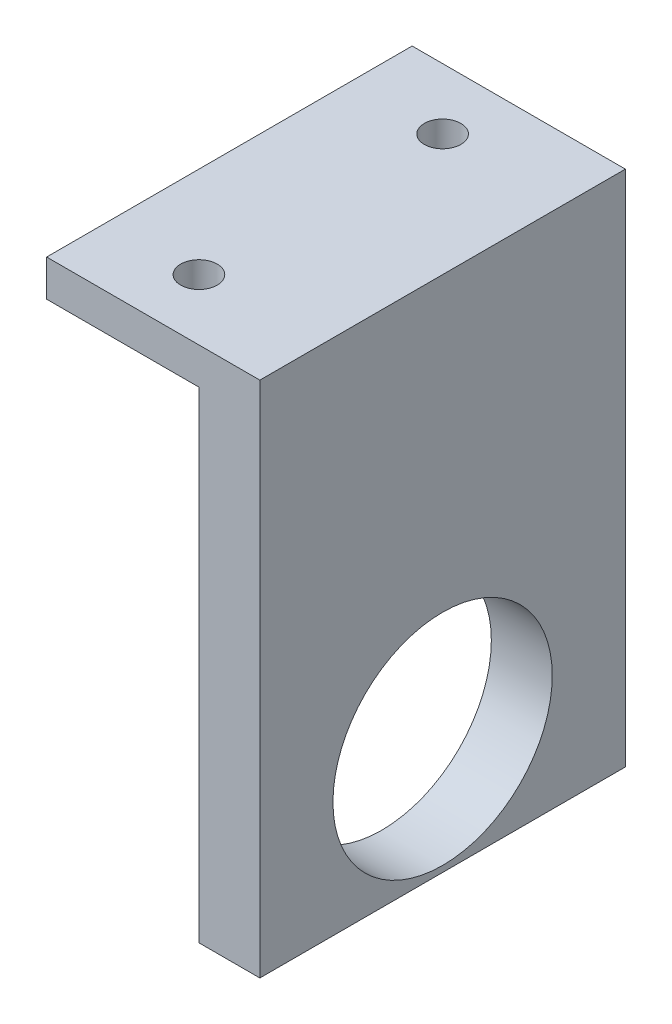
SolidWorks part; units mm, degrees
ref_plane "前视基准面" through (0, 0, 0) normal (0, 0, 1) x (1, 0, 0)
ref_plane "上视基准面" through (0, 0, 0) normal (0, 1, 0) x (1, 0, 0)
ref_plane "右视基准面" through (0, 0, 0) normal (1, 0, 0) x (0, 0, -1)
other "Configuration Table"
sketch "草图1" plane through (0, 0, 0) normal (1, 0, 0) x (0, 0, -1)
  line L0 (-15, -28.5) -> (-15, 11)
  line L2 (-15, 11) -> (15, 11)
  line L3 (15, -28.5) -> (15, 11)
  line L4 (-15, -28.5) -> (15, 11) construction
  line L5 (-15, 11) -> (15, -28.5) construction
  line L6 (-15, -28.5) -> (15, -28.5)
  point P0 (0, 0)
  point P2 (0, 0)
extrude "凸台-拉伸1" add sketch "草图1" along normal blind 5 contours L2 L3 L6 L0
sketch3d "3D草图1"
  point P0 (5, -2.7495, 2.7495)
ref_plane "基准面1" through (5, 0, 0) normal (1, 0, 0) x (0, 0, -1)
sketch "草图2" plane through (5, 0, 0) normal (1, 0, 0) x (0, 0, -1)
  circle A0 centre (0, -19) radius 9
extrude "切除-拉伸1" cut sketch "草图2" against normal blind 5
sketch3d "3D草图2"
  point P0 (2.9808, 11, -3.1847)
ref_plane "基准面2" through (0, 11, 0) normal (0, 1, 0) x (1, 0, 0)
sketch "草图3" plane through (0, 11, 0) normal (0, 1, 0) x (1, 0, 0)
  line L1 (5, -15) -> (-12.5, -15)
  line L2 (5, 15) -> (-12.5, 15)
  line L3 (-12.5, 15) -> (-12.5, -15)
  line L4 (5, 15) -> (5, -15)
extrude "凸台-拉伸2" add sketch "草图3" along normal blind 3
sketch3d "3D草图3"
  point P0 (-6.2094, 14, 4.3134)
ref_plane "基准面4" through (0, 14, 0) normal (0, 1, 0) x (1, 0, 0)
sketch "草图6" plane through (0, 14, 0) normal (0, 1, 0) x (1, 0, 0)
  circle A0 centre (-5, 10) radius 1.5
  circle A1 centre (-5, -10) radius 1.5
extrude "切除-拉伸2" cut sketch "草图6" against normal blind 3
